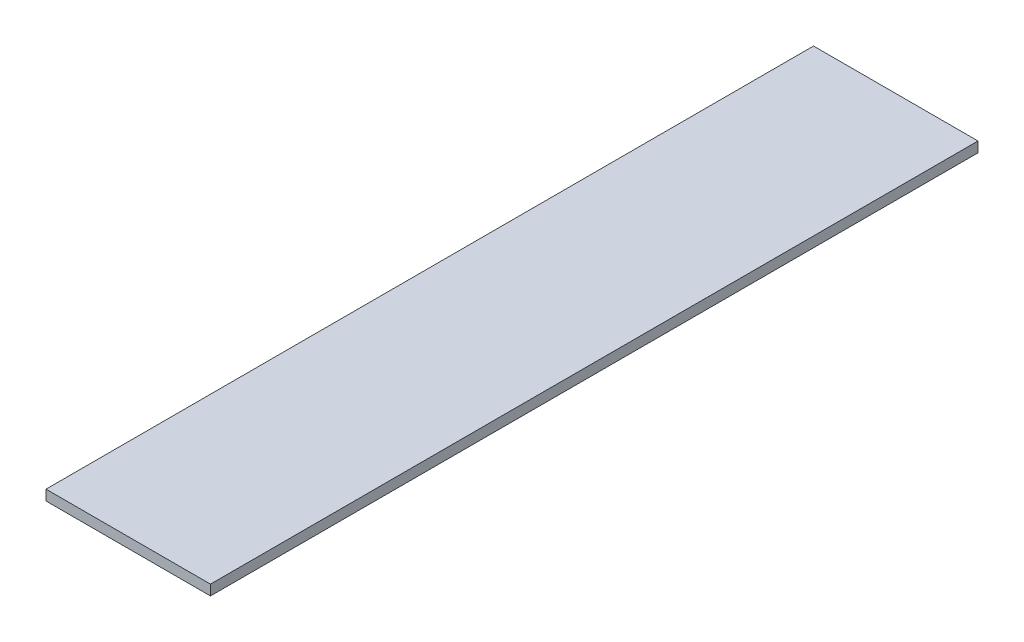
SolidWorks part; units mm, degrees
material "Maple"
ref_plane "Front Plane" through (0, 0, 0) normal (0, 0, 1) x (1, 0, 0)
ref_plane "Top Plane" through (0, 0, 0) normal (0, 1, 0) x (1, 0, 0)
ref_plane "Right Plane" through (0, 0, 0) normal (1, 0, 0) x (0, 0, -1)
sketch "Sketch1" plane through (0, 0, 0) normal (0, 1, 0) x (1, 0, 0)
  line L1 (-76.2, 355.6) -> (76.2, 355.6)
  line L2 (-76.2, 355.6) -> (-76.2, -355.6)
  line L3 (-76.2, -355.6) -> (76.2, -355.6)
  line L4 (76.2, 355.6) -> (76.2, -355.6)
  line L5 (-76.2, 355.6) -> (76.2, -355.6) construction
  line L6 (-76.2, -355.6) -> (76.2, 355.6) construction
  point P0 (0, 0)
  dimension "D1" = 152.4
  dimension "D2" = 711.2
extrude "Boss-Extrude1" add sketch "Sketch1" along normal blind 9.525
